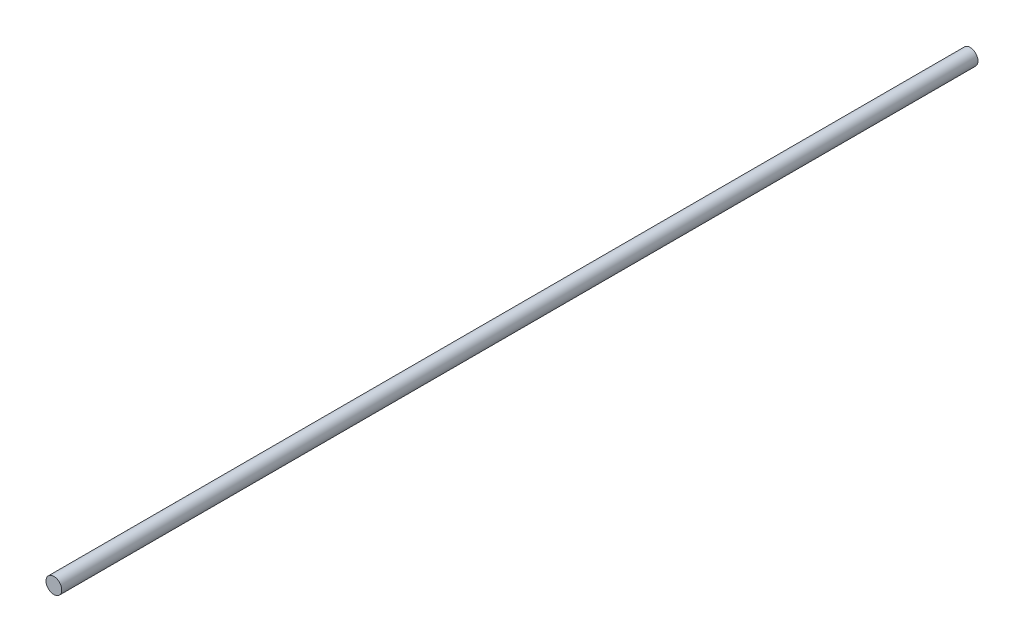
SolidWorks part; units mm, degrees
material " Aluminum"
ref_plane "Front Plane" through (0, 0, 0) normal (0, 0, 1) x (1, 0, 0)
ref_plane "Top Plane" through (0, 0, 0) normal (0, 1, 0) x (1, 0, 0)
ref_plane "Right Plane" through (0, 0, 0) normal (1, 0, 0) x (0, 0, -1)
sketch "Sketch1" plane through (0, 0, 0) normal (0, 0, 1) x (1, 0, 0)
  circle A0 centre (0, 0) radius 3.175
  dimension "D1" = 6.35
extrude "Boss-Extrude1" add sketch "Sketch1" along normal blind 368.8092
equation "\"Force\" = 300'lbf"
equation "\"Elastic_modulus\" = 9860000'psi"
equation "\"Diameter\"= 0.25in"
equation "\"Max Deflection\"= 0.009in"
equation "\"Area\"= ( pi / 4 ) * ( \"Diameter\" ) ^ 2"
equation "\"Length\"= \"Max Deflection\" * \"Area\" * \"Elastic_modulus\" / \"Force\""
equation "\"Yield Strength\"= 40000"
equation "\"D1@Sketch1\"=\"Diameter\""
equation "\"D1@Boss-Extrude1\"=\"Length\""
